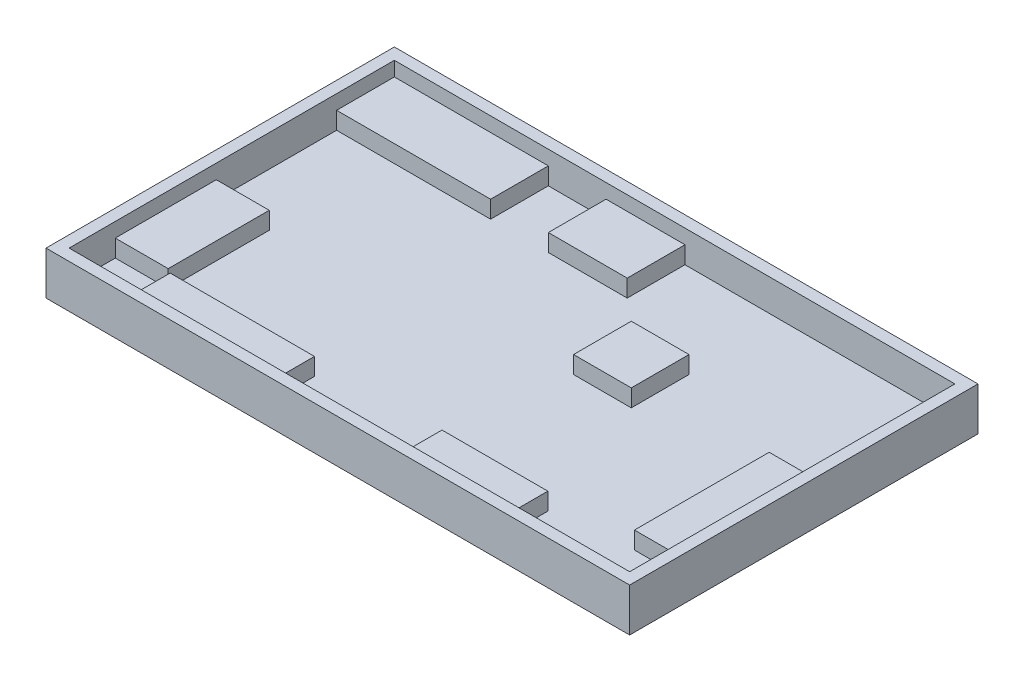
SolidWorks part; units mm, degrees
ref_plane "Front Plane" through (0, 0, 0) normal (0, 0, 1) x (1, 0, 0)
ref_plane "Top Plane" through (0, 0, 0) normal (0, 1, 0) x (1, 0, 0)
ref_plane "Right Plane" through (0, 0, 0) normal (1, 0, 0) x (0, 0, -1)
sketch "Sketch1" plane through (0, 0, 0) normal (0, 1, 0) x (1, 0, 0)
  line L0 (-1.2, 35) -> (59.45, 35) construction
  line L1 (0, 0) -> (58.25, 0) construction
  line L2 (0, 0) -> (0, 33.8) construction
  line L3 (0, 33.8) -> (58.25, 33.8) construction
  line L4 (58.25, 0) -> (58.25, 33.8) construction
  line L5 (59.45, -1.2) -> (59.45, 35) construction
  line L6 (-1.2, -1.2) -> (59.45, -1.2) construction
  line L7 (-1.2, -1.2) -> (-1.2, 35) construction
  dimension "D1" = 58.25
  dimension "D2" = 33.8
  dimension "D3" = 1.2
sketch "Sketch2" plane through (0, 0, 0) normal (0, 1, 0) x (1, 0, 0)
  line L1 (-1.2, 35) -> (59.45, 35)
  line L2 (-1.2, 35) -> (-1.2, -1.2)
  line L3 (-1.2, -1.2) -> (59.45, -1.2)
  line L4 (59.45, 35) -> (59.45, -1.2)
extrude "Boss-Extrude1" add sketch "Sketch2" along normal blind 1.2
sketch "Sketch3" plane through (0, 1.2, 0) normal (0, 1, 0) x (1, 0, 0)
  line L1 (-1.2, 35) -> (59.45, 35)
  line L2 (-1.2, 35) -> (-1.2, -1.2)
  line L3 (-1.2, -1.2) -> (59.45, -1.2)
  line L4 (59.45, 35) -> (59.45, -1.2)
  line L5 (0, 33.8) -> (58.25, 33.8)
  line L6 (0, 33.8) -> (0, 0)
  line L7 (0, 0) -> (58.25, 0)
  line L8 (58.25, 33.8) -> (58.25, 0)
extrude "Boss-Extrude2" add sketch "Sketch3" along normal blind 3.3
sketch "Sketch4" plane through (0, 1.2, 0) normal (0, 1, 0) x (1, 0, 0)
  line L0 (0, 0) -> (58.25, 0) construction
  line L1 (0, 33.8) -> (16, 33.8)
  line L2 (0, 33.8) -> (0, 27.8)
  line L3 (0, 27.8) -> (16, 27.8)
  line L4 (16, 33.8) -> (16, 27.8)
  line L5 (0, 4.8) -> (5.5, 4.8)
  line L6 (0, 4.8) -> (0, 15.3)
  line L7 (0, 15.3) -> (5.5, 15.3)
  line L8 (5.5, 4.8) -> (5.5, 15.3)
  line L9 (0, 0) -> (0, 33.8) construction
  line L10 (58.25, 0) -> (58.25, 33.8) construction
  line L11 (34.25, 0) -> (45.25, 0)
  line L12 (34.25, 0) -> (34.25, 4.5)
  line L13 (34.25, 4.5) -> (45.25, 4.5)
  line L14 (45.25, 0) -> (45.25, 4.5)
  line L15 (0, 33.8) -> (58.25, 33.8) construction
  line L16 (6, 0) -> (21, 0)
  line L17 (6, 0) -> (6, 4.5)
  line L18 (6, 4.5) -> (21, 4.5)
  line L19 (21, 0) -> (21, 4.5)
  line L20 (58.25, 5.5) -> (53.25, 5.5)
  line L21 (58.25, 5.5) -> (58.25, 19.5)
  line L22 (58.25, 19.5) -> (53.25, 19.5)
  line L23 (53.25, 5.5) -> (53.25, 19.5)
  line L24 (22, 33.8) -> (30.2, 33.8)
  line L25 (22, 33.8) -> (22, 27.8)
  line L26 (22, 27.8) -> (30.2, 27.8)
  line L27 (30.2, 33.8) -> (30.2, 27.8)
  line L29 (34.29, 24.13) -> (40.29, 24.13)
  line L30 (34.29, 24.13) -> (34.29, 18.13)
  line L31 (34.29, 18.13) -> (40.29, 18.13)
  line L32 (40.29, 24.13) -> (40.29, 18.13)
  point P11 (0, 10.05)
  dimension "D1" = 16
  dimension "D2" = 6
  dimension "D3" = 4.8
  dimension "D4" = 10.5
  dimension "D5" = 5.5
  dimension "D6" = 13
  dimension "D7" = 11
  dimension "D8" = 4.5
  dimension "D9" = 6
  dimension "D10" = 15
  dimension "D11" = 4.5
  dimension "D12" = 5.5
  dimension "D13" = 14
  dimension "D14" = 5
  dimension "D15" = 22
  dimension "D16" = 8.2
  dimension "D17" = 6
  dimension "D18" = 6
extrude "Boss-Extrude3" add sketch "Sketch4" along normal blind 1.8
